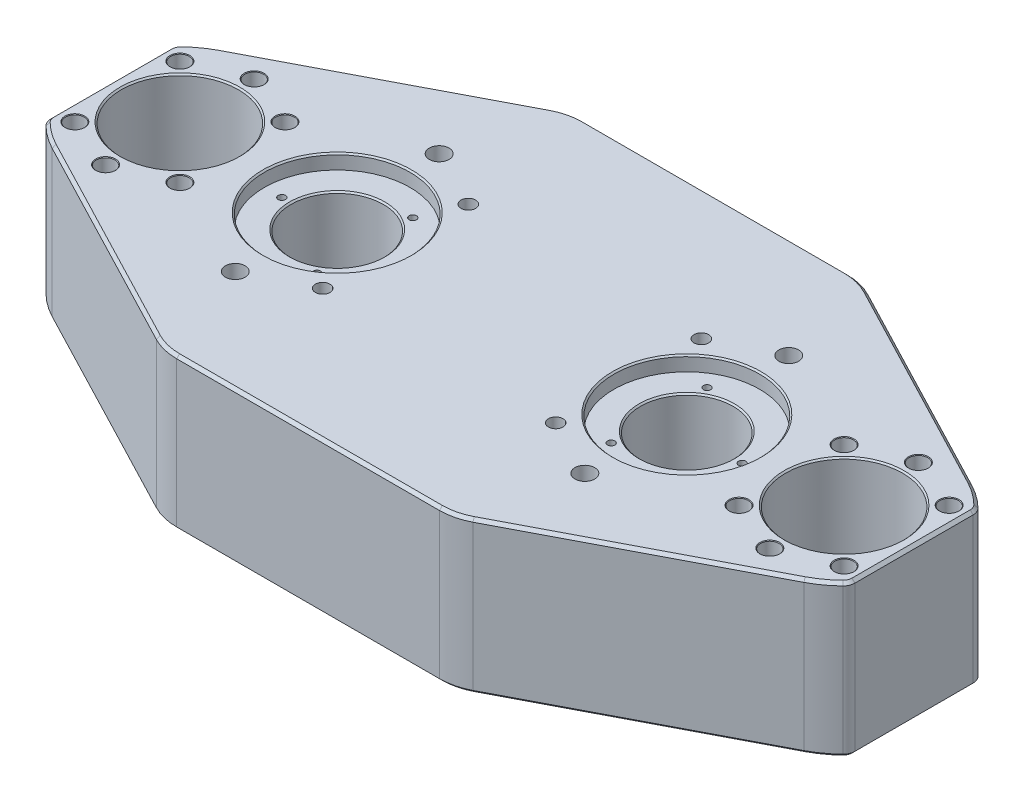
SolidWorks part; units mm, degrees
material "6061-T6 Aluminum"
ref_plane "Front Plane" through (0, 0, 0) normal (0, 0, 1) x (1, 0, 0)
ref_plane "Top Plane" through (0, 0, 0) normal (0, 1, 0) x (1, 0, 0)
ref_plane "Right Plane" through (0, 0, 0) normal (1, 0, 0) x (0, 0, -1)
sketch "Sketch1" plane through (0, 0, 0) normal (0, 1, 0) x (1, 0, 0)
  line L0 (114, 0) -> (0, 0) construction
  line L1 (0, 0) -> (-114, 0) construction
  line L2 (-60, 0) -> (0, 0) construction
  line L3 (0, 0) -> (60, 0) construction
  line L18 (0, 70) -> (0, 0) construction
  line L19 (0, 0) -> (0, -70) construction
  line L20 (-129.0194, 28.8213) -> (-54.3441, 67.7362)
  line L21 (-45.1014, 70) -> (45.1014, 70)
  line L22 (54.3441, 67.7362) -> (129.0194, 28.8213)
  line L23 (-129.0194, -28.8213) -> (-54.3441, -67.7362)
  line L24 (-45.1014, -70) -> (45.1014, -70)
  line L25 (54.3441, -67.7362) -> (129.0194, -28.8213)
  line L26 (-138, 20.3039) -> (-138, -20.3039)
  line L27 (138, 20.3039) -> (138, -20.3039)
  line L28 (-138, 0) -> (-114, 0) construction
  line L29 (114, 0) -> (138, 0) construction
  circle A0 centre (-114, 0) radius 20.1
  circle A1 centre (114, 0) radius 20.1
  circle A2 centre (-60, 0) radius 15.875
  circle A3 centre (60, 0) radius 15.875
  arc A6 (-54.3441, -67.7362) -> (-45.1014, -70) centre (-45.1014, -50) ccw
  arc A7 (45.1014, -70) -> (54.3441, -67.7362) centre (45.1014, -50) ccw
  arc A8 (-129.0194, 28.8213) -> (-136.807, 23.1536) centre (-114, 0) ccw
  arc A9 (129.0194, -28.8213) -> (136.807, -23.1536) centre (114, 0) ccw
  arc A10 (45.1014, 70) -> (54.3441, 67.7362) centre (45.1014, 50) cw
  arc A11 (-54.3441, 67.7362) -> (-45.1014, 70) centre (-45.1014, 50) cw
  arc A12 (-136.807, -23.1536) -> (-129.0194, -28.8213) centre (-114, 0) ccw
  arc A13 (136.807, 23.1536) -> (129.0194, 28.8213) centre (114, 0) ccw
  arc A14 (136.807, -23.1536) -> (138, -20.3039) centre (134, -20.3039) ccw
  arc A15 (136.807, 23.1536) -> (138, 20.3039) centre (134, 20.3039) cw
  arc A16 (-136.807, -23.1536) -> (-138, -20.3039) centre (-134, -20.3039) cw
  arc A17 (-136.807, 23.1536) -> (-138, 20.3039) centre (-134, 20.3039) ccw
  point P30 (-50, -70)
  point P36 (50, 70)
  point P39 (-50, 70)
  dimension "D1" = 40.2
  dimension "D3" = 120
  dimension "D7" = 31.75
  dimension "D8" = 20
  dimension "D6" = 32.5
  dimension "D9" = 276
  dimension "D10" = 4
  dimension "D11" = 32.5
  dimension "D2" = 228
  dimension "D4" = 140
  dimension "D5" = 100
extrude "Boss-Extrude1" add sketch "Sketch1" along normal mid plane 52
sketch "Sketch7" plane through (0, -26, 0) normal (0, -1, 0) x (1, 0, 0)
  circle A0 centre (95.9688, 18.0312) radius 3.3 construction
  circle A1 centre (114, 25.5) radius 3.3 construction
  circle A2 centre (132.0312, 18.0312) radius 3.3 construction
  circle A3 centre (132.0312, -18.0312) radius 3.3 construction
  circle A4 centre (114, -25.5) radius 3.3 construction
  circle A5 centre (95.9688, -18.0312) radius 3.3 construction
  circle A6 centre (95.9688, 18.0312) radius 3.3
  circle A7 centre (114, 25.5) radius 3.3
  circle A8 centre (132.0312, 18.0312) radius 3.3
  circle A9 centre (132.0312, -18.0312) radius 3.3
  circle A10 centre (114, -25.5) radius 3.3
  circle A11 centre (95.9688, -18.0312) radius 3.3
hole_wizard "M6 Clearance Hole1" positions "Sketch8" profile "Sketch9" hole size "M6" standard "ANSI Metric" end condition through all
sketch "Sketch8" plane through (0, -26, 0) normal (0, -1, 0) x (-1, 0, 0)
  point P0 (-95.9688, -18.0312)
  point P3 (-114, -25.5)
  point P6 (-132.0312, -18.0312)
  point P9 (-132.0312, 18.0312)
  point P12 (-114, 25.5)
  point P15 (-95.9688, 18.0312)
sketch "Sketch9" plane through (95.9688, -26, 18.0312) normal (1, 0, 0) x (0, 0, -1)
  line L0 (0, 0) -> (0, 52)
  line L1 (0, 52) -> (3.2, 52)
  line L2 (3.2, 52) -> (3.2, 0)
  line L5 (3.2, 0) -> (0, 0)
  line L11 (0, -6.35) -> (0, 107.95) construction
  dimension "Thru Hole Dia." = 6.4
  dimension "Thru Hole Depth" = 52
mirror "Mirror5" about plane through (0, 0, 0) normal (1, 0, 0) of "M6 Clearance Hole1"
chamfer "Chamfer2" distance 0.5 angle 45 4 edges at (114, 26, 20.1) (114, -26, 20.1) (-114, -26, 20.1) (-114, 26, 20.1)
chamfer "Chamfer3" [suppressed] distance 1 angle 45
chamfer "Chamfer5" distance 1 angle 45 40 edges at (91.6818, -26, -48.2787) (-91.6818, -26, -48.2787) (49.8594, -26, -69.4258) (-49.8594, -26, -69.4258) (0, -26, -70) (-133.1243, -26, -26.2776) (133.1243, -26, 26.2776) (-91.6818, -26, 48.2787) (91.6818, -26, 48.2787) (-49.8594, -26, 69.4258) (49.8594, -26, 69.4258) (0, -26, 70) (91.6818, 26, -48.2787) (-91.6818, 26, -48.2787) (49.8594, 26, -69.4258) (-49.8594, 26, -69.4258) (0, 26, -70) (-133.1243, 26, -26.2776) (133.1243, 26, 26.2776) (-91.6818, 26, 48.2787) (91.6818, 26, 48.2787) (-49.8594, 26, 69.4258) (49.8594, 26, 69.4258) (0, 26, 70) (133.1243, -26, -26.2776) (-133.1243, -26, 26.2776) (133.1243, 26, -26.2776) (-133.1243, 26, 26.2776) (-137.6897, -26, -21.8486) (137.6897, -26, -21.8486) (-138, -26, 0) (138, -26, 0) (-137.6897, -26, 21.8486) (137.6897, -26, 21.8486) (-137.6897, 26, -21.8486) (137.6897, 26, -21.8486) (-138, 26, 0) (138, 26, 0) (-137.6897, 26, 21.8486) (137.6897, 26, 21.8486)
chamfer "Chamfer6" distance 0.5 angle 45 4 edges at (60, -26, 15.875) (60, 26, 15.875) (-60, -26, 15.875) (-60, 26, 15.875)
sketch "Sketch10" plane through (0, 26, 0) normal (0, 1, 0) x (1, 0, 0)
  line L0 (50.5, -16.4545) -> (50.5, 16.4545) construction
  line L1 (50.5, 16.4545) -> (79, 0) construction
  line L2 (79, 0) -> (50.5, -16.4545) construction
  circle A3 centre (50.5, -16.4545) radius 1.7
  circle A4 centre (50.5, 16.4545) radius 1.7
  circle A5 centre (79, 0) radius 1.7
  circle A6 centre (60, 0) radius 19 construction
  dimension "D1" = 38
hole_wizard "M3x0.5 Tapped Hole1" positions "Sketch11" profile "Sketch13" tap size "M3x0.5" standard "ANSI Metric"
sketch "Sketch11" plane through (0, 26, 0) normal (0, 1, 0) x (1, 0, 0)
  point P0 (79, 0)
  point P3 (50.5, -16.4545)
  point P6 (50.5, 16.4545)
sketch "Sketch13" plane through (79, 26, 0) normal (1, 0, 0) x (0, 0, 1)
  line L0 (0, 0) -> (0, 12.7511)
  line L1 (0, 12.7511) -> (1.25, 12)
  line L2 (1.25, 12) -> (1.25, 0)
  line L5 (1.25, 0) -> (0, 0)
  line L10 (0, 12.7511) -> (-1.25, 12) construction
  line L11 (0, -6.35) -> (0, 107.95) construction
  dimension "Tap Drill Dia." = 2.5
  dimension "Tap Drill Depth" = 12
  dimension "Drill Angle" = 118
cosmetic thread "Hole Thread9" parameters "D1"=10, "D2"=3
cosmetic thread "Hole Thread13" parameters "D1"=10, "D2"=3
cosmetic thread "Hole Thread14" parameters "D1"=10, "D2"=3
mirror "Mirror6" about plane through (0, 0, 0) normal (1, 0, 0) of "M3x0.5 Tapped Hole1"
mirror "Mirror7" about plane through (0, 0, 0) normal (0, 1, 0) of "Mirror6", "M3x0.5 Tapped Hole1"
sketch "Sketch14" plane through (0, -26, 0) normal (0, -1, 0) x (1, 0, 0)
  line L0 (-60, 0) -> (-60, -35) construction
  circle A1 centre (-60, -35) radius 3.25
  dimension "D1" = 35
chamfer "Chamfer9" distance 0.2 angle 45 24 edges at (-132.0312, -26, -21.2312) (-132.0312, 26, -21.2312) (-114, -26, -28.7) (-114, 26, -28.7) (-95.9688, -26, -21.2312) (-95.9688, 26, -21.2312) (-95.9688, -26, 14.8312) (-95.9688, 26, 14.8312) (-114, -26, 22.3) (-114, 26, 22.3) (-132.0312, -26, 14.8312) (-132.0312, 26, 14.8312) (132.0312, -26, 14.8312) (132.0312, 26, 14.8312) (114, -26, 22.3) (114, 26, 22.3) (95.9688, -26, 14.8312) (95.9688, 26, 14.8312) (95.9688, -26, -21.2312) (95.9688, 26, -21.2312) (132.0312, -26, -21.2312) (132.0312, 26, -21.2312) (114, -26, -28.7) (114, 26, -28.7)
sketch "Sketch15" plane through (0, -26, 0) normal (0, -1, 0) x (1, 0, 0)
  circle A1 centre (-60, -35) radius 3.05
  point P0 (-60, -35)
hole_wizard "M8x1.25 Tapped Hole1" positions "Sketch15" profile "Sketch16" tap size "M8x1.25" standard "ANSI Metric" end condition through all
cosmetic thread "Hole Thread15" parameters "D2"=8
sketch "Sketch16" plane through (-60, -26, -35) normal (1, 0, 0) x (0, 0, -1)
  line L0 (0, 0) -> (0, 52)
  line L1 (0, 52) -> (3.4, 52)
  line L2 (3.4, 52) -> (3.4, 0)
  line L5 (3.4, 0) -> (0, 0)
  line L11 (0, -6.35) -> (0, 107.95) construction
  dimension "Thru Tap Drill Dia." = 6.8
  dimension "Thru Tap Drill Depth" = 52
mirror "Mirror8" about plane through (0, 0, 0) normal (0, 0, 1) of "M8x1.25 Tapped Hole1"
mirror "Mirror9" about plane through (0, 0, 0) normal (1, 0, 0) of "Mirror8", "M8x1.25 Tapped Hole1"
sketch "Sketch17" plane through (0, 26, 0) normal (0, 1, 0) x (1, 0, 0)
  circle A0 centre (60, 0) radius 25
  circle A1 centre (-60, 0) radius 25
  dimension "D1" = 50
  dimension "D2" = 50
extrude "Cut-Extrude1" cut sketch "Sketch17" against normal blind 5
mirror "Mirror10" about plane through (0, 0, 0) normal (0, 1, 0) of "Cut-Extrude1"
chamfer "Chamfer10" distance 0.5 angle 45 8 edges at (60, -21, -15.875) (60, 21, 15.875) (-60, -21, -15.875) (-60, 21, 15.875) (60, -26, 25) (-60, -26, 25) (60, 26, 25) (-60, 26, 25)
sketch "Sketch18" plane through (0, -26, 0) normal (0, -1, 0) x (1, 0, 0)
  line L1 (-40, -25) -> (40, -25) construction
  line L2 (-40, -25) -> (-40, 25) construction
  line L3 (-40, 25) -> (40, 25) construction
  line L4 (40, -25) -> (40, 25) construction
  line L5 (-40, -25) -> (40, 25) construction
  line L6 (-40, 25) -> (40, -25) construction
  point P0 (0, 0)
  dimension "D1" = 50
  dimension "D2" = 80
sketch "Sketch19" plane through (0, -26, 0) normal (0, -1, 0) x (-1, 0, 0)
  point P0 (40, 25)
  point P3 (40, -25)
  point P6 (-40, 25)
  point P9 (-40, -25)
hole_wizard "M6x1.0 Tapped Hole1" positions "Sketch19" profile "Sketch20" tap size "M6x1.0" standard "ANSI Metric"
sketch "Sketch20" plane through (-40, -26, -25) normal (1, 0, 0) x (0, 0, -1)
  line L0 (0, 0) -> (0, 16.5022)
  line L1 (0, 16.5022) -> (2.5, 15)
  line L2 (2.5, 15) -> (2.5, 0)
  line L5 (2.5, 0) -> (0, 0)
  line L10 (0, 16.5022) -> (-2.5, 15) construction
  line L11 (0, -6.35) -> (0, 107.95) construction
  dimension "Tap Drill Dia." = 5
  dimension "Tap Drill Depth" = 15
  dimension "Drill Angle" = 118
cosmetic thread "Hole Thread16" parameters "D1"=12, "D2"=6
cosmetic thread "Hole Thread17" parameters "D1"=12, "D2"=6
cosmetic thread "Hole Thread18" parameters "D1"=12, "D2"=6
cosmetic thread "Hole Thread19" parameters "D1"=12, "D2"=6
mirror "Mirror11" about plane through (0, 0, 0) normal (0, 1, 0) of "M6x1.0 Tapped Hole1"
